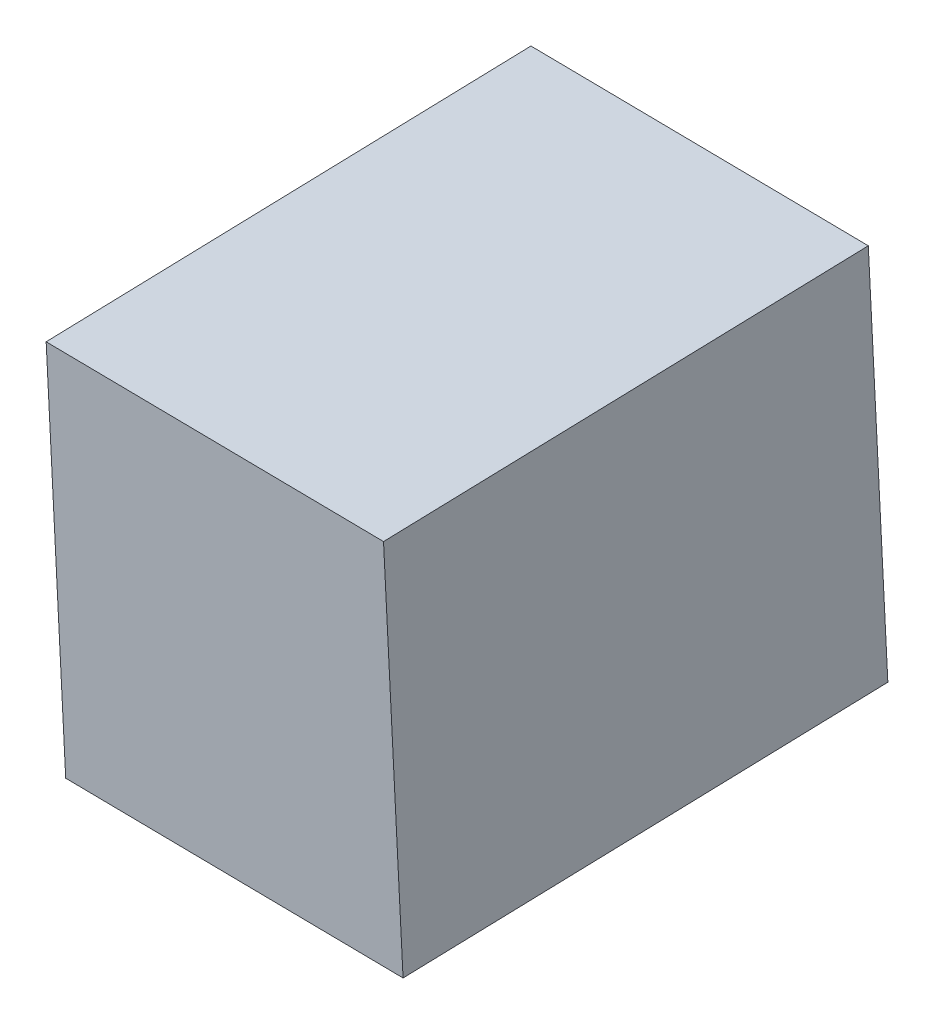
SolidWorks part; units mm, degrees
ref_plane "Front Plane" through (0, 0, 0) normal (0, 0, 1) x (1, 0, 0)
ref_plane "Top Plane" through (0, 0, 0) normal (0, 1, 0) x (1, 0, 0)
ref_plane "Right Plane" through (0, 0, 0) normal (1, 0, 0) x (0, 0, -1)
sketch "Sketch1" plane through (-407.5239, -1.7737, -6.9132) normal (0.9998, 0.0044, 0.017) x (0.017, 0, -0.9999)
  line L5 (-575.2268, 44.9856) -> (-573.1772, 0.0286)
  line L6 (-573.1772, 0.0286) -> (-517.6058, 2.5621)
  line L7 (-573.1772, 0.0286) -> (-423.3328, 6.8599) construction
  line L8 (-517.6058, 2.5621) -> (-519.6554, 47.5191)
  line L10 (-519.6554, 47.5191) -> (-575.2268, 44.9856)
extrude "Boss-Extrude1" add sketch "Sketch1" along normal blind 40
hole_wizard "M10x1.25 Tapped Hole1" positions "Sketch2" profile "Sketch3" tap size "M10x1.25" standard "ANSI Metric"
sketch "Sketch2" plane through (-407.5239, -1.7737, -6.9132) normal (-0.9998, -0.0044, -0.017) x (-0.017, 0, 0.9999)
  point P0 (564.0984, 20.4633)
  point P3 (539.1244, 21.6018)
sketch "Sketch3" plane through (-417.1808, 18.6686, 557.1033) normal (-0.0151, 0.707, 0.707) x (-0.0089, -0.7072, 0.707)
  line L0 (0, 0) -> (0, 12.6438)
  line L1 (0, 12.6438) -> (4.4, 10)
  line L2 (4.4, 10) -> (4.4, 0)
  line L5 (4.4, 0) -> (0, 0)
  line L10 (0, 12.6438) -> (-4.4, 10) construction
  line L11 (0, -6.35) -> (0, 107.95) construction
  dimension "Tap Drill Dia." = 8.8
  dimension "Tap Drill Depth" = 10
  dimension "Drill Angle" = 118
